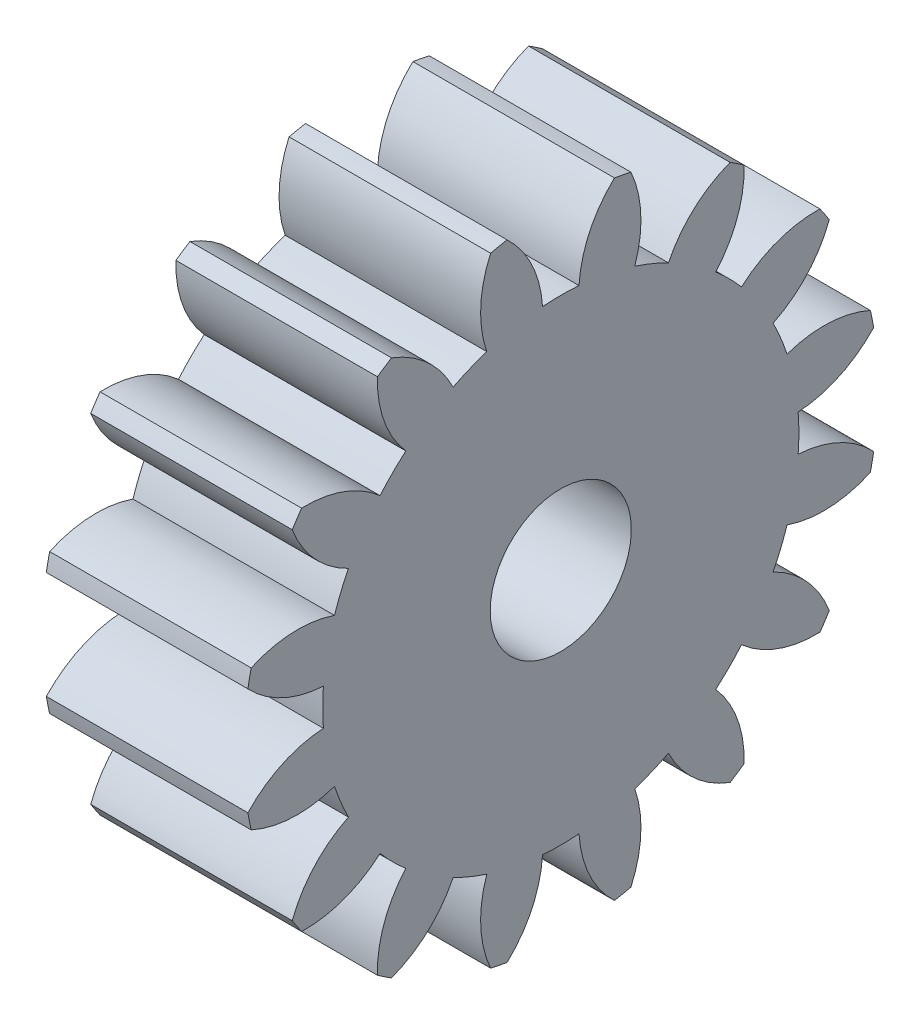
SolidWorks part; units mm, degrees
ref_plane "Plane1" through (0, 0, 0) normal (0, 0, 1) x (1, 0, 0)
ref_plane "Plane2" through (0, 0, 0) normal (0, 1, 0) x (1, 0, 0)
ref_plane "Plane3" through (0, 0, 0) normal (1, 0, 0) x (0, 0, -1)
sketch "HoldingSke" plane through (0, 0, 0) normal (0, 1, 0) x (1, 0, 0)
  line L0 (0, 0) -> (0.2746, -0.0788)
  line L1 (-15, 0) -> (100, 0) construction
  line L2 (0, 0) -> (-2.1039, 2.3779)
  line L3 (0, 0) -> (-11.863, 4.5341)
  line L4 (0, 0) -> (8.3015, 2.3804)
  line L5 (0, 0) -> (-46.8476, -17.4728)
  line L6 (0, 0) -> (-16.5793, -11.1861)
  line L7 (-2.1039, 2.3779) -> (8.6586, 51.2059)
  line L8 (-76.2, 54.61) -> (-73.9, 54.61)
  line L9 (-71.009, 38.7566) -> (-53.1078, 45.2721)
  line L10 (-76.2, 71.12) -> (104.1128, 71.12)
  line L11 (0, 0) -> (-20, 0)
  line L12 (-76.2, 101.6) -> (-76.083, 101.6)
  line L13 (24.9733, 27.94) -> (52.9518, 28.4284)
  line L14 (24.9733, 27.94) -> (24.9743, 27.94)
  line L15 (24.9733, 27.94) -> (100.4006, 29.5858)
  line L16 (-63.627, -3.5) -> (-12.827, -3.5)
  circle A0 centre (0, 0) radius 7
  circle A1 centre (0, 0) radius 23.624
  circle A2 centre (0, 0) radius 37.5
  circle A3 centre (0, 0) radius 7
  dimension "Hub_dia" = 75
  dimension "Pitch" = 0.2857
  dimension "Overall_len" = 50
  dimension "Thickness" = 20
  dimension "OAL" = 50.0001
  dimension "Ap" = 20
  dimension "H" = 19.05
  dimension "Pitch_radius" = 180.3128
  dimension "Width" = 20
  dimension "Backlash" = 0.117
  dimension "Addendum_fac" = 1
  dimension "Dedendum_fac" = 1.25
  dimension "Clearance_fac" = 0.25
  dimension "Dedendum_add" = 0.001
  dimension "Module" = 3.5
sketch "BasProSke" plane through (0, 0, 0) normal (0, 1, 0) x (1, 0, 0)
  line L0 (-10, 0) -> (60, 0) construction
  line L1 (0, 0) -> (0, 31.5)
  line L2 (0, 0) -> (20, 0)
  line L3 (20, 0) -> (20, 31.5)
  line L4 (20, 31.5) -> (0, 31.5)
  dimension "Thickness" = 20
revolve "Base-Revolve" add sketch "BasProSke" angle 360 about L0
sketch "TooCutSke" plane through (0, 0, 0) normal (1, 0, 0) x (0, 0, -1)
  line L1 (0, 0) -> (0, 107) construction
  line L2 (0, 0) -> (-2.9491, 27.8443) construction
  line L3 (0, 0) -> (-10.88, 54.6976) construction
  line L4 (-2.9491, 27.8443) -> (-5.44, 27.3488) construction
  arc A0 (1.8098, 23.5546) -> (-1.8098, 23.5546) centre (0, 0) ccw
  arc A1 (5.3469, 31.0687) -> (-5.3469, 31.0687) centre (0, 0) ccw
  circle A2 centre (0, 0) radius 28 construction
  circle A3 centre (0, 0) radius 26.3114 construction
  arc A4 (-1.8098, 23.5546) -> (-5.3469, 31.0687) centre (-12.9895, 22.8815) ccw
  arc A5 (5.3469, 31.0687) -> (1.8098, 23.5546) centre (12.9895, 22.8815) ccw
extrude "ToothCut" cut sketch "TooCutSke" along normal through all
fillet "Breaks" [suppressed] radius 0.07
fillet "RootFillets" [suppressed] radius 0.876
pattern_circular "TeethCuts" count 16 every 22.5 about axis through (-10, 0, 0) along (1, 0, 0) of "ToothCut", "RootFillets", "Breaks"
sketch "HubNeaOneSke" plane through (0, 0, 0) normal (-1, 0, 0) x (0, 0, 1)
  circle A0 centre (0, 0) radius 23.624
extrude "HubNearOne" [suppressed] add sketch "HubNeaOneSke" along normal blind 30.0001
sketch "HubNeaBotSke" plane through (0, 0, 0) normal (-1, 0, 0) x (0, 0, 1)
  circle A0 centre (0, 0) radius 23.624
extrude "HubNearBoth" [suppressed] add sketch "HubNeaBotSke" along normal blind 15
ref_plane "FarPln" through (20, 0, 0) normal (1, 0, 0) x (0, 0, -1)
sketch "HubFarSke" plane through (20, 0, 0) normal (1, 0, 0) x (0, 0, -1)
  circle A0 centre (0, 0) radius 23.624
extrude "HubFar" [suppressed] add sketch "HubFarSke" along normal blind 15
sketch "BorSke" plane through (0, 0, 0) normal (1, 0, 0) x (0, 0, -1)
  circle A0 centre (0, 0) radius 7
extrude "Bore" cut sketch "BorSke" along normal mid plane 100.0001
sketch "KeySke" plane through (0, 0, 0) normal (1, 0, 0) x (0, 0, -1)
  line L0 (-2.5, 0) -> (-2.5, 9.3)
  line L1 (-2.5, 9.3) -> (2.5, 9.3)
  line L2 (2.5, 9.3) -> (2.5, 0)
  line L3 (0, 0) -> (0, 34) construction
  line L4 (-2.5, 0) -> (2.5, 0)
extrude "Keyway" [suppressed] cut sketch "KeySke" along normal mid plane 100.0001
pattern_circular "Keyway2" [suppressed] count 2 every 90 about axis through (-10, 0, 0) along (1, 0, 0)
equation "' \"Module@HoldingSke\" = 6.35"
equation "' \"Num_teeth@HoldingSke\" = 12"
equation "' \"Ap@HoldingSke\" =  20"
equation "' \"Ap@HoldingSke\" = 20"
equation "' \"Width@HoldingSke\" = 0.5 * 25.4"
equation "' \"Hub_dia@HoldingSke\"= 1 * 25.4"
equation "' \"Hub_dia@HoldingSke\" = 1 * 25.4"
equation "' \"Overall_len@HoldingSke\" = 1.0 * 25.4"
equation "' \"Bore@HoldingSke\" = 0.75 * 25.4"
equation "' \"T_dim@HoldingSke\" = 0.1 * 25.4"
equation "' \"Width@KeySke\" = 0.25 * 25.4"
equation "' \"Show_teeth@HoldingSke\" = 13"
equation "' \"Backlash@HoldingSke\" = 0.009 * 25.4"
equation "' \"Addendum_fac@HoldingSke\" = 1.0"
equation "' \"Dedendum_fac@HoldingSke\" = 1.25"
equation "' \"Dedendum_add@HoldingSke\" = 0.00005 * 25.4"
equation "' \"Clearance_fac@HoldingSke\" = 0.25"
equation "\"Pitch@HoldingSke\" = 1 / \"Module@HoldingSke\""
equation "\"Overcut_dia@TooCutSke\" = (\"Num_teeth@HoldingSke\" + 2 * \"Addendum_fac@HoldingSke\") / \"Pitch@HoldingSke\" + 0.002 * 25.4"
equation "\"Pitch_dia@TooCutSke\" = \"Num_teeth@HoldingSke\" / \"Pitch@HoldingSke\""
equation "\"Base_dia@TooCutSke\" = \"Num_teeth@HoldingSke\" / \"Pitch@HoldingSke\" * cos((\"Ap@HoldingSke\"  * 3.14159265 / 180))"
equation "\"Root_dia@TooCutSke\" = (\"Num_teeth@HoldingSke\" + 2) / \"Pitch@HoldingSke\" - 2 * (\"Addendum_fac@HoldingSke\" + \"Dedendum_fac@HoldingSke\") / \"Pitch@HoldingSke\" - \"Dedendum_add@HoldingSke\" * 2"
equation "\"Half_ang@TooCutSke\" = 180 / \"Num_teeth@HoldingSke\""
equation "\"Half_CT@TooCutSke\" = \"Num_teeth@HoldingSke\" / \"Pitch@HoldingSke\" * sin((3.14159265 / 2 / \"Num_teeth@HoldingSke\")) / 2 - 7 * \"Backlash@HoldingSke\" / 4"
equation "\"Flank_rad@TooCutSke\" = \"Num_teeth@HoldingSke\" / \"Pitch@HoldingSke\" / 5"
equation "\"Radius@RootFillets\" = \"Clearance_fac@HoldingSke\" / \"Pitch@HoldingSke\" + \"Dedendum_add@HoldingSke\""
equation "\"Break_rad@Breaks\" = 0.02 / \"Pitch@HoldingSke\""
equation "\"Thickness@HoldingSke\" = \"Width@HoldingSke\""
equation "\"OAL@HoldingSke\" = \"Thickness@HoldingSke\""
equation "\"MHD@HoldingSke\" = (\"Num_teeth@HoldingSke\" + 2) / \"Pitch@HoldingSke\" - 2 * (\"Addendum_fac@HoldingSke\" + \"Dedendum_fac@HoldingSke\")  / \"Pitch@HoldingSke\" - \"Dedendum_add@HoldingSke\" * 2"
equation "\"MBD@HoldingSke\" = (\"Num_teeth@HoldingSke\" + 2) / \"Pitch@HoldingSke\" - 2 * (\"Addendum_fac@HoldingSke\" + \"Dedendum_fac@HoldingSke\")  / \"Pitch@HoldingSke\" - \"Dedendum_add@HoldingSke\" * 2 - 0.002 * 25.4"
equation "\"MHD@HoldingSke\" = ((sgn( \"MHD@HoldingSke\" - \"Hub_dia@HoldingSke\" )-1)*( \"MHD@HoldingSke\" - \"Hub_dia@HoldingSke\" ))/-2+ \"Hub_dia@HoldingSke\""
equation "\"MBD@HoldingSke\" = ((sgn( \"MBD@HoldingSke\" - \"Bore@HoldingSke\" )-1)*( \"MBD@HoldingSke\" - \"Bore@HoldingSke\" ))/-2+ \"Bore@HoldingSke\""
equation "\"OAL@HoldingSke\" = ((sgn( \"OAL@HoldingSke\" - \"Overall_len@HoldingSke\" )+1)*( \"OAL@HoldingSke\" - \"Overall_len@HoldingSke\" ))/2 + \"Overall_len@HoldingSke\" + 0.000002 * 25.4"
equation "\"Num_teeth@TeethCuts\" = int( \"Show_teeth@HoldingSke\" ) + 1"
equation "\"Num_teeth@TeethCuts\" = ((sgn( \"Num_teeth@TeethCuts\" - \"Num_teeth@HoldingSke\" )-1)*( \"Num_teeth@TeethCuts\" - \"Num_teeth@HoldingSke\" ))/-2+ \"Num_teeth@HoldingSke\""
equation "\"Num_teeth@TeethCuts\" = ((sgn( \"Num_teeth@TeethCuts\" - 2.0)+1)*( \"Num_teeth@TeethCuts\" - 2.0))/2 +2.0"
equation "\"Angle@TeethCuts\" = 360.0 / \"Num_teeth@HoldingSke\""
equation "\"Diameter@BasProSke\" = (\"Num_teeth@HoldingSke\" + 2 * \"Addendum_fac@HoldingSke\") / \"Pitch@HoldingSke\""
equation "\"Thickness@BasProSke\"  = \"Thickness@HoldingSke\""
equation "' \"Fillet_rad@BasProSke\" =  \"Thickness@HoldingSke\" * 0.05"
equation "' \"Fillet_rad@BasProSke\" = \"Thickness@HoldingSke\" * 0.05"
equation "\"MHD@HoldingSke\" = ((sgn( \"MHD@HoldingSke\" - \"Root_dia@TooCutSke\" )-1)*( \"MHD@HoldingSke\" - \"Root_dia@TooCutSke\" ))/-2+ \"Root_dia@TooCutSke\""
equation "\"Diameter@HubNeaOneSke\" = \"MHD@HoldingSke\""
equation "\"Length@HubNearOne\" = \"OAL@HoldingSke\" - \"Thickness@BasProSke\""
equation "\"Diameter@HubNeaBotSke\" = \"MHD@HoldingSke\""
equation "\"Length@HubNearBoth\" = ( \"OAL@HoldingSke\" - \"Thickness@BasProSke\" ) / 2.0"
equation "\"Thickness@FarPln\" = \"Thickness@BasProSke\""
equation "\"Diameter@HubFarSke\" = \"MHD@HoldingSke\""
equation "\"Length@HubFar\" = ( \"OAL@HoldingSke\" - \"Thickness@BasProSke\" ) / 2.0"
equation "\"Diameter@BorSke\" = \"MBD@HoldingSke\""
equation "\"D1@Bore\" = \"OAL@HoldingSke\" * 2.0"
equation "\"D1@Keyway\" = \"OAL@HoldingSke\" * 2.0"
equation "\"Offset@KeySke\" = \"T_dim@HoldingSke\" + \"MBD@HoldingSke\" / 2.0"
